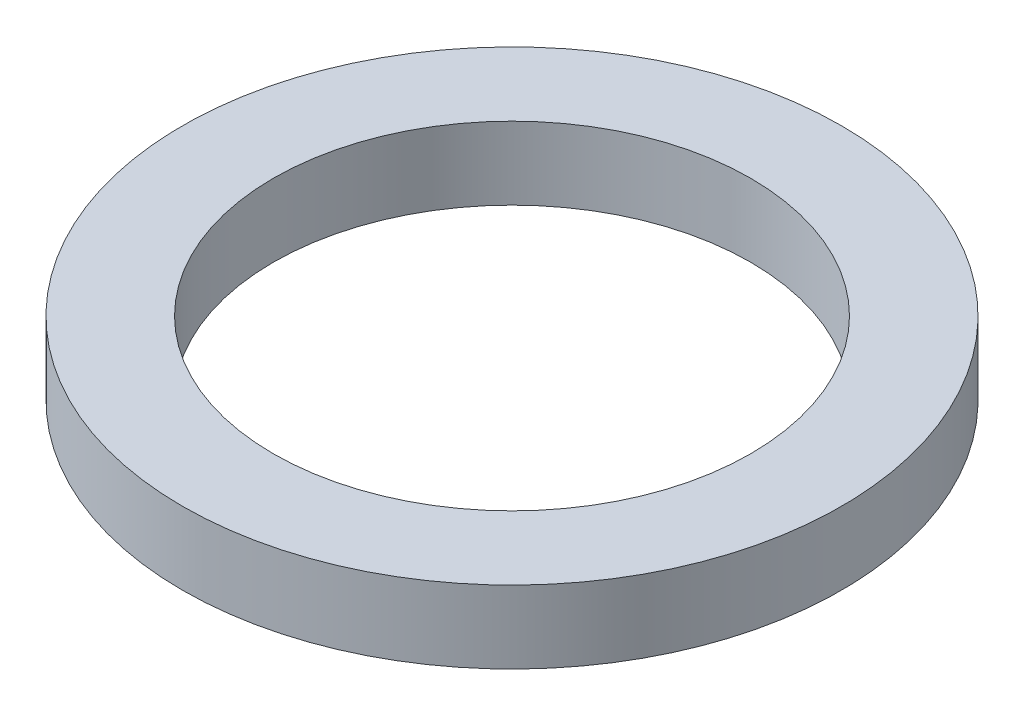
SolidWorks part; units mm, degrees
ref_plane "Front Plane" through (0, 0, 0) normal (0, 0, 1) x (1, 0, 0)
ref_plane "Top Plane" through (0, 0, 0) normal (0, 1, 0) x (1, 0, 0)
ref_plane "Right Plane" through (0, 0, 0) normal (1, 0, 0) x (0, 0, -1)
sketch "Sketch1" plane through (0, 0, 0) normal (0, 1, 0) x (1, 0, 0)
  circle A0 centre (0, 0) radius 8.3344
  circle A1 centre (0, 0) radius 11.5094
  dimension "D1" = 16.6687
  dimension "D2" = 3.175
extrude "Boss-Extrude1" add sketch "Sketch1" along normal blind 2.54
